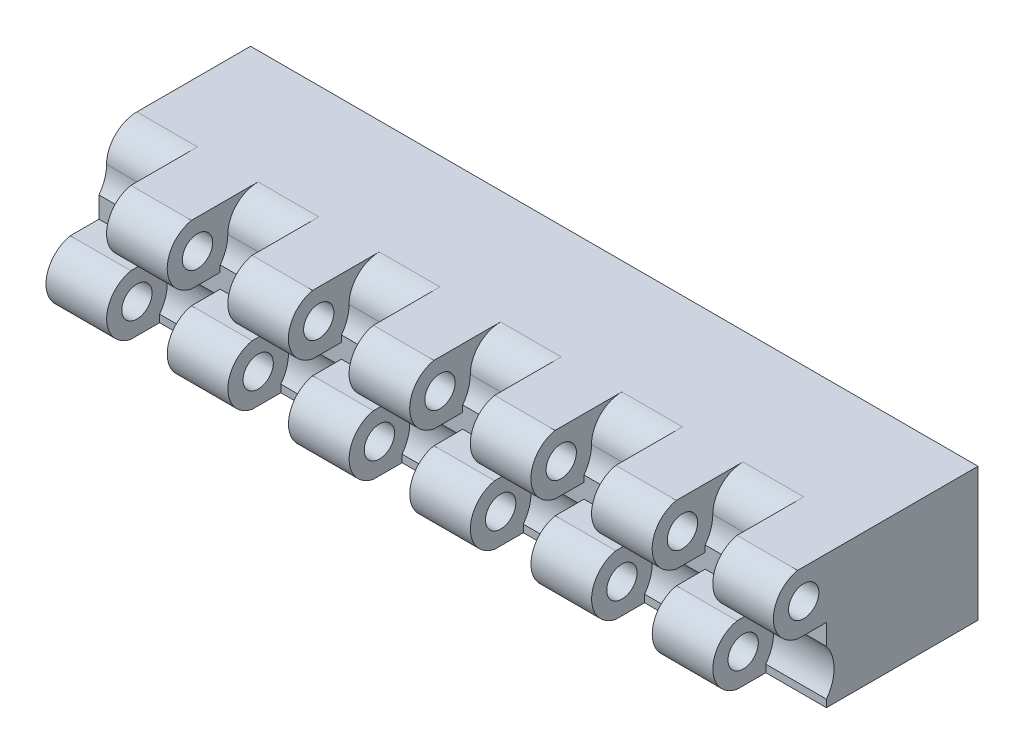
SolidWorks part; units mm, degrees
ref_plane "Front Plane" through (0, 0, 0) normal (0, 0, 1) x (1, 0, 0)
ref_plane "Top Plane" through (0, 0, 0) normal (0, 1, 0) x (1, 0, 0)
ref_plane "Right Plane" through (0, 0, 0) normal (1, 0, 0) x (0, 0, -1)
sketch "Sketch1" plane through (0, 0, 0) normal (1, 0, 0) x (0, 0, -1)
  line L1 (-12.5, 11) -> (12.5, 11)
  line L2 (-12.5, 11) -> (-12.5, -11)
  line L3 (-12.5, -11) -> (12.5, -11)
  line L4 (12.5, 11) -> (12.5, -11)
  line L5 (-12.5, 11) -> (12.5, -11) construction
  line L6 (-12.5, -11) -> (12.5, 11) construction
  point P0 (0, 0)
  dimension "D1" = 22
  dimension "D2" = 25
extrude "Boss-Extrude1" add sketch "Sketch1" along normal mid plane 120
sketch "Sketch5" plane through (60, 0, 0) normal (1, 0, 0) x (0, 0, -1)
  line L0 (-12.5, 11) -> (-12.5, 1.01) construction
  line L1 (-12.5, 11) -> (-12.5, -11) construction
  line L2 (-12.5, 6.005) -> (-17.5, 6.005) construction
  line L3 (-13.7433, 11) -> (-11.25, 11)
  line L7 (-11.25, 6.005) -> (-11.25, 11)
  arc A1 (-13.7433, 11) -> (-11.25, 6.005) centre (-17.5, 6.005) ccw
  dimension "D1" = 5
extrude "Cut-Extrude2" cut sketch "Sketch5" against normal up to next
sketch "Sketch6" plane through (-60, 0, 0) normal (-1, 0, 0) x (0, 0, 1)
  line L0 (12.5, -11) -> (12.5, -1.01) construction
  line L1 (12.5, 2.255) -> (12.5, -11) construction
  line L2 (12.5, -6.005) -> (17.5, -6.005) construction
  circle A0 centre (17.5, -6.005) radius 6.26
  dimension "D2" = 5
  dimension "D1" = 9.99
extrude "Cut-Extrude3" cut sketch "Sketch6" against normal up to next
fillet "Fillet1" radius 5 1 edges at (0, 11, 11.25)
sketch "Sketch2" plane through (60, 0, 0) normal (1, 0, 0) x (0, 0, -1)
  line L0 (-17.25, 1.202) -> (-6, 1.202)
  line L1 (-12.5, -11) -> (-12.5, 1.202) construction
  line L13 (-6, 11) -> (-6, 1.202)
  line L14 (-17.25, 11) -> (-6, 11)
  arc A1 (-17.25, 11) -> (-17.25, 1.202) centre (-16.25, 6.101) ccw
  circle A2 centre (-16.25, 6.101) radius 2.5
  dimension "D3" = 5
  dimension "D1" = 2.5
  dimension "D2" = 11.25
  dimension "D4" = 5
extrude "Boss-Extrude2" add sketch "Sketch2" against normal blind 10
pattern_linear "LPattern1" count 6 spacing 20 along (-1, 0, 0) of "Boss-Extrude2"
sketch "Sketch3" plane through (-60, 0, 0) normal (-1, 0, 0) x (0, 0, 1)
  line L0 (10.99, -1.202) -> (17.24, -1.202)
  line L1 (17.24, -11) -> (10.99, -11)
  line L8 (10.99, -11) -> (10.99, -1.202)
  arc A1 (17.24, -11) -> (17.24, -1.202) centre (16.24, -6.101) ccw
  circle A2 centre (16.24, -6.101) radius 2.5
  arc A3 (12.5, -2.2384) -> (12.5, -9.7716) centre (17.5, -6.005) ccw construction
  point P7 (12.24, -0.3112)
  point P8 (11.24, -6.005)
  dimension "D2" = 4
  dimension "D3" = 5
  dimension "D4" = 2.5
  dimension "D1" = 6.25
  dimension "D5" = 5
extrude "Boss-Extrude3" add sketch "Sketch3" against normal blind 10
pattern_linear "LPattern2" count 6 spacing 20 along (1, 0, 0) of "Boss-Extrude3"
sketch "Sketch4" plane through (0, 0, -12.5) normal (0, 0, -1) x (-1, 0, 0)
  circle A0 centre (0, 0) radius 7
  dimension "D1" = 14
extrude "Cut-Extrude1" cut sketch "Sketch4" against normal blind 15
